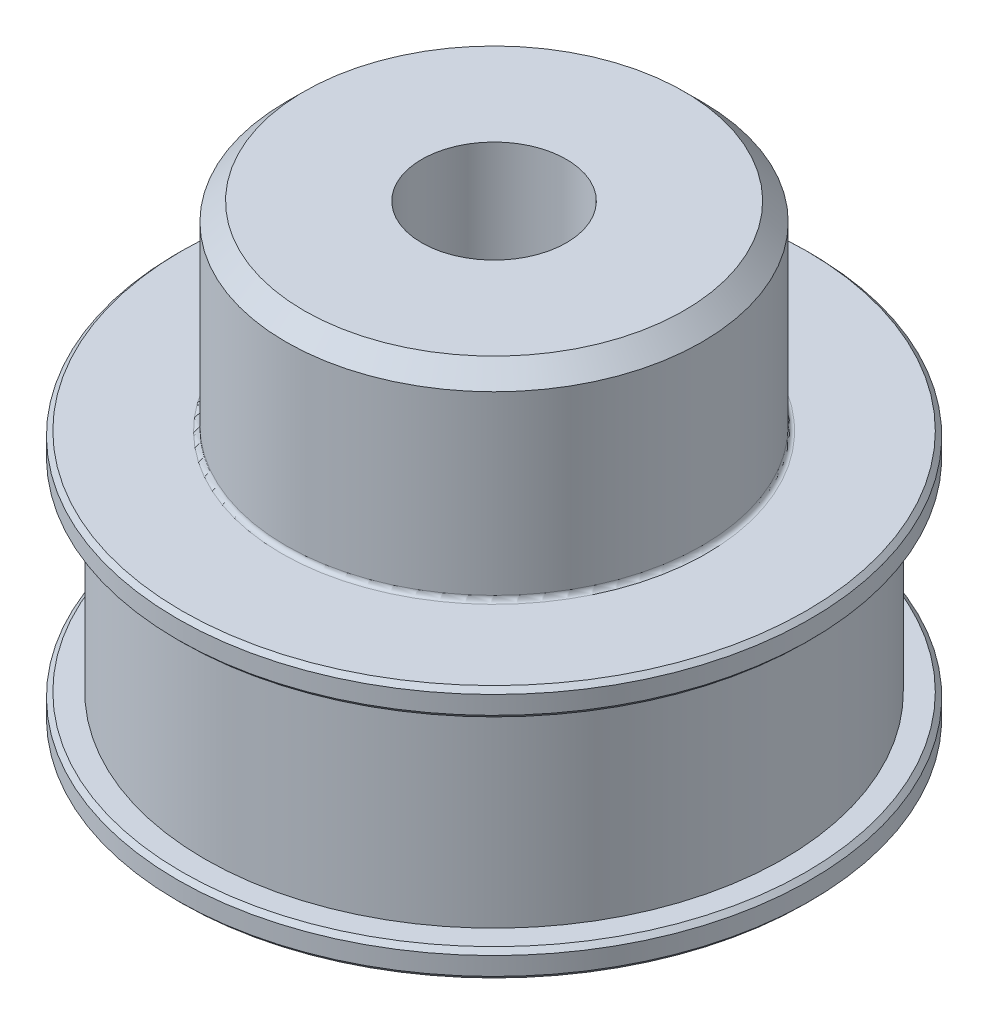
SolidWorks part; units mm, degrees
ref_plane "Front Plane" through (0, 0, 0) normal (0, 0, 1) x (1, 0, 0)
ref_plane "Top Plane" through (0, 0, 0) normal (0, 1, 0) x (1, 0, 0)
ref_plane "Right Plane" through (0, 0, 0) normal (1, 0, 0) x (0, 0, -1)
sketch "Sketch1" plane through (0, 0, 0) normal (0, 1, 0) x (1, 0, 0)
  circle A0 centre (0, 0) radius 17.5
  dimension "D1" = 35
extrude "Boss-Extrude1" add sketch "Sketch1" along normal blind 1.5
sketch "Sketch2" plane through (0, 1.5, 0) normal (0, 1, 0) x (1, 0, 0)
  circle A0 centre (0, 0) radius 16
  dimension "D1" = 32
extrude "Boss-Extrude2" add sketch "Sketch2" along normal blind 11
sketch "Sketch3" plane through (0, 12.5, 0) normal (0, 1, 0) x (1, 0, 0)
  circle A0 centre (0, 0) radius 17.5
  circle A1 centre (0, 0) radius 17.5 construction
extrude "Boss-Extrude3" add sketch "Sketch3" along normal blind 1.5
sketch "Sketch4" plane through (0, 14, 0) normal (0, 1, 0) x (1, 0, 0)
  circle A0 centre (0, 0) radius 11.5
  dimension "D1" = 23
extrude "Boss-Extrude4" add sketch "Sketch4" along normal blind 11
sketch "Sketch6" plane through (0, 25, 0) normal (0, 1, 0) x (1, 0, 0)
  circle A0 centre (0, 0) radius 4
  dimension "D1" = 8
extrude "Cut-Extrude1" cut sketch "Sketch6" against normal through all and the other way through all
chamfer "Chamfer1" distance 1 angle 45 1 edges at (0, 25, 11.5)
chamfer "Chamfer2" distance 0.25 angle 45 4 edges at (0, 0, 17.5) (0, 1.5, 17.5) (0, 12.5, 17.5) (0, 14, 17.5)
fillet "Fillet1" radius 0.25 1 edges at (0, 14, 11.5)
